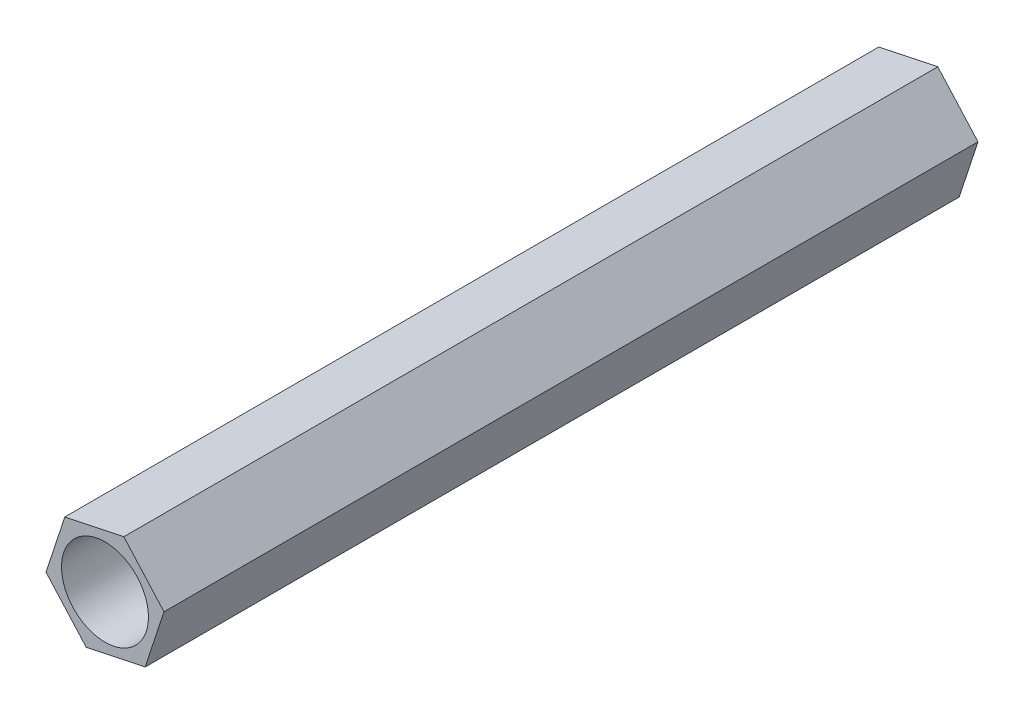
SolidWorks part; units mm, degrees
material "Copper"
ref_plane "Front Plane" through (0, 0, 0) normal (0, 0, 1) x (1, 0, 0)
ref_plane "Top Plane" through (0, 0, 0) normal (0, 1, 0) x (1, 0, 0)
ref_plane "Right Plane" through (0, 0, 0) normal (1, 0, 0) x (0, 0, -1)
sketch "Sketch1" plane through (0, 0, 0) normal (0, 0, 1) x (1, 0, 0)
  line L1 (3.3908, 0.7087) -> (1.0816, 3.2909)
  line L2 (1.0816, 3.2909) -> (-2.3092, 2.5822)
  line L3 (-2.3092, 2.5822) -> (-3.3908, -0.7087)
  line L4 (-3.3908, -0.7087) -> (-1.0816, -3.2909)
  line L5 (-1.0816, -3.2909) -> (2.3092, -2.5822)
  line L6 (2.3092, -2.5822) -> (3.3908, 0.7087)
  circle A0 centre (0, 0) radius 3 construction
  dimension "D1" = 6
extrude "Boss-Extrude4" add sketch "Sketch1" along normal blind 46.8
sketch "Sketch4" plane through (0, 0, 46.8) normal (0, 0, 1) x (1, 0, 0)
  circle A0 centre (0, 0) radius 2.5
extrude "Cut-Extrude3" cut sketch "Sketch4" against normal blind 15
sketch "Sketch5" plane through (0, 0, 0) normal (0, 0, -1) x (-1, 0, 0)
  circle A0 centre (0, 0) radius 2.5
extrude "Cut-Extrude4" cut sketch "Sketch5" against normal blind 15
